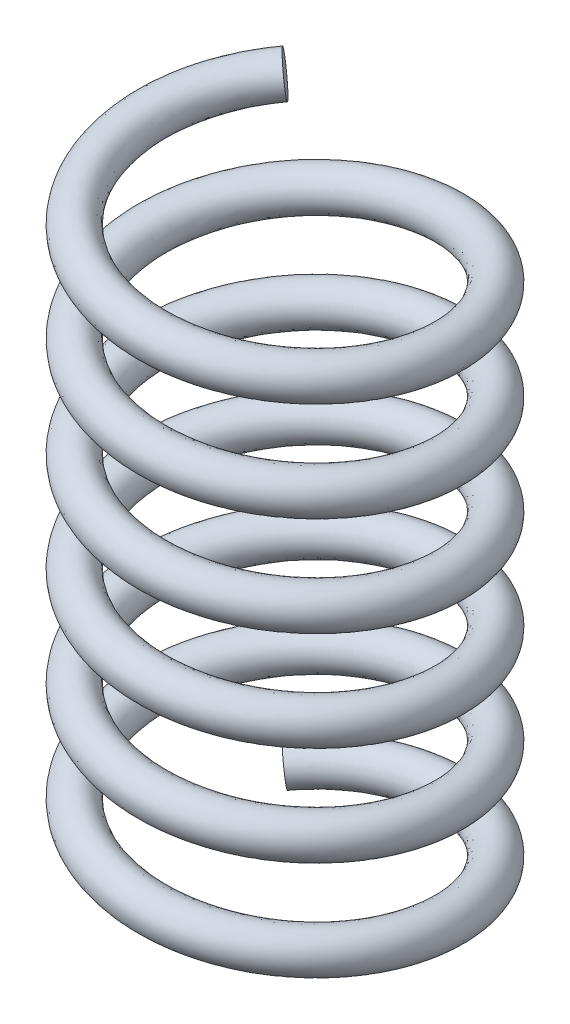
SolidWorks part; units mm, degrees
material "可锻铸铁"
ref_plane "前视基准面" through (0, 0, 0) normal (0, 0, 1) x (1, 0, 0)
ref_plane "上视基准面" through (0, 0, 0) normal (0, 1, 0) x (1, 0, 0)
ref_plane "右视基准面" through (0, 0, 0) normal (1, 0, 0) x (0, 0, -1)
sketch "草图1" plane through (0, 0, 0) normal (0, 1, 0) x (1, 0, 0)
  circle A0 centre (0, 0) radius 7.5
  dimension "D1" = 15
curve "螺旋线/涡状线1" pitch 5 height 30 turns 6
ref_plane "基准面1" through (-5.3033, 0, -5.3033) normal (0.7032, 0.1055, -0.7032) x (-0.6983, 0.2886, -0.655)
sketch "草图2" plane through (-5.3033, 0, -5.3033) normal (0.7032, 0.1055, -0.7032) x (-0.6983, 0.2886, -0.655)
  circle A0 centre (0, 0) radius 1
  dimension "D1" = 2
sweep "扫描1" add profiles "草图2" path "螺旋线/涡状线1"
